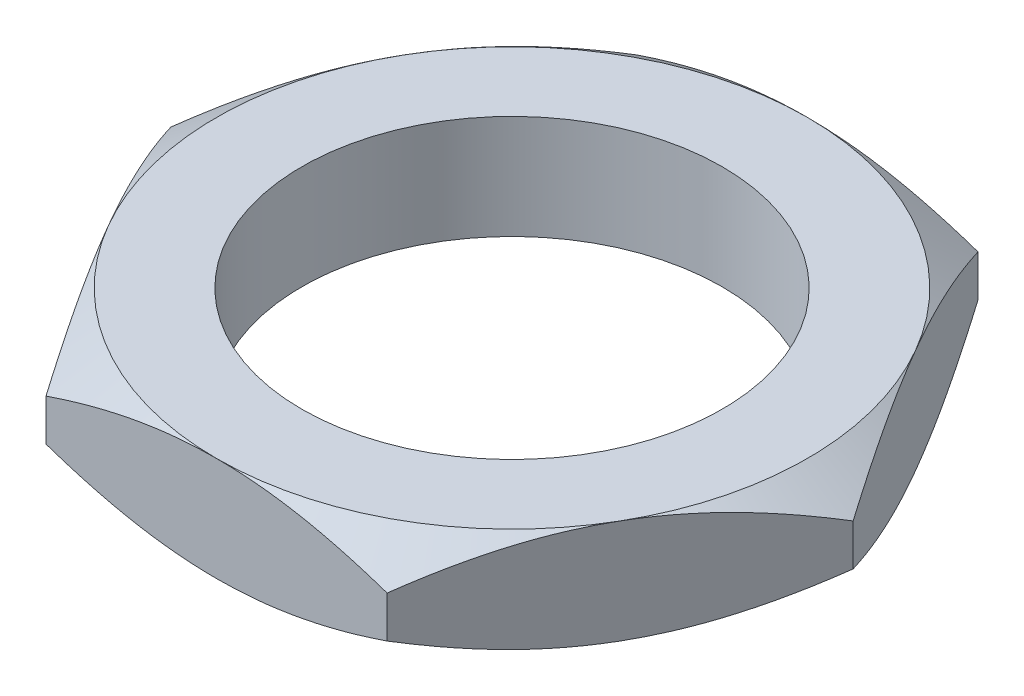
SolidWorks part; units mm, degrees
ref_plane "Ebene vorne" through (0, 0, 0) normal (0, 0, 1) x (1, 0, 0)
ref_plane "Ebene oben" through (0, 0, 0) normal (0, 1, 0) x (1, 0, 0)
ref_plane "Ebene rechts" through (0, 0, 0) normal (1, 0, 0) x (0, 0, -1)
sketch "Skizze1" plane through (0, 0, 0) normal (0, 1, 0) x (1, 0, 0)
  line L1 (8.1984, 0) -> (4.0992, 7.1)
  line L2 (4.0992, 7.1) -> (-4.0992, 7.1)
  line L3 (-4.0992, 7.1) -> (-8.1984, 0)
  line L4 (-8.1984, 0) -> (-4.0992, -7.1)
  line L5 (-4.0992, -7.1) -> (4.0992, -7.1)
  line L6 (4.0992, -7.1) -> (8.1984, 0)
  circle A0 centre (0, 0) radius 7.1 construction
  circle A1 centre (0, 0) radius 5.05
  dimension "D2" = 10.1
  dimension "D1" = 14.2
extrude "Aufsatz-Linear austragen1" add sketch "Skizze1" along normal blind 2.5
ref_plane "Ebene1" through (0, 0, 0) normal (0.866, 0, 0.5) x (0.5, 0, -0.866)
ref_plane "Ebene2" through (0, 1.25, 0) normal (0, 1, 0) x (1, 0, 0)
sketch "Skizze4" plane through (0, 0, 0) normal (0.866, 0, 0.5) x (0.5, 0, -0.866)
  line L0 (-8.1984, 0.75) -> (-7.1, 0)
  line L1 (-8.1984, 2.5) -> (-8.1984, 0) construction
  line L2 (-8.1984, 0) -> (-4.0992, 0) construction
  line L3 (-7.1, 0) -> (-8.1984, 0)
  line L4 (-8.1984, 0) -> (-8.1984, 0.75)
  line L5 (0, 0) -> (0, 2.5) construction
  line L6 (-4.0992, 2.5) -> (4.0992, 2.5) construction
  line L7 (-8.1984, 1.25) -> (0, 1.25) construction
  dimension "D1" = 14.2
  dimension "D2" = 1
revolve "Schnitt-Rotation1" cut sketch "Skizze4" angle 360 about L5
mirror "Spiegeln1" about plane through (0, 1.25, 0) normal (0, 1, 0) of "Schnitt-Rotation1"
